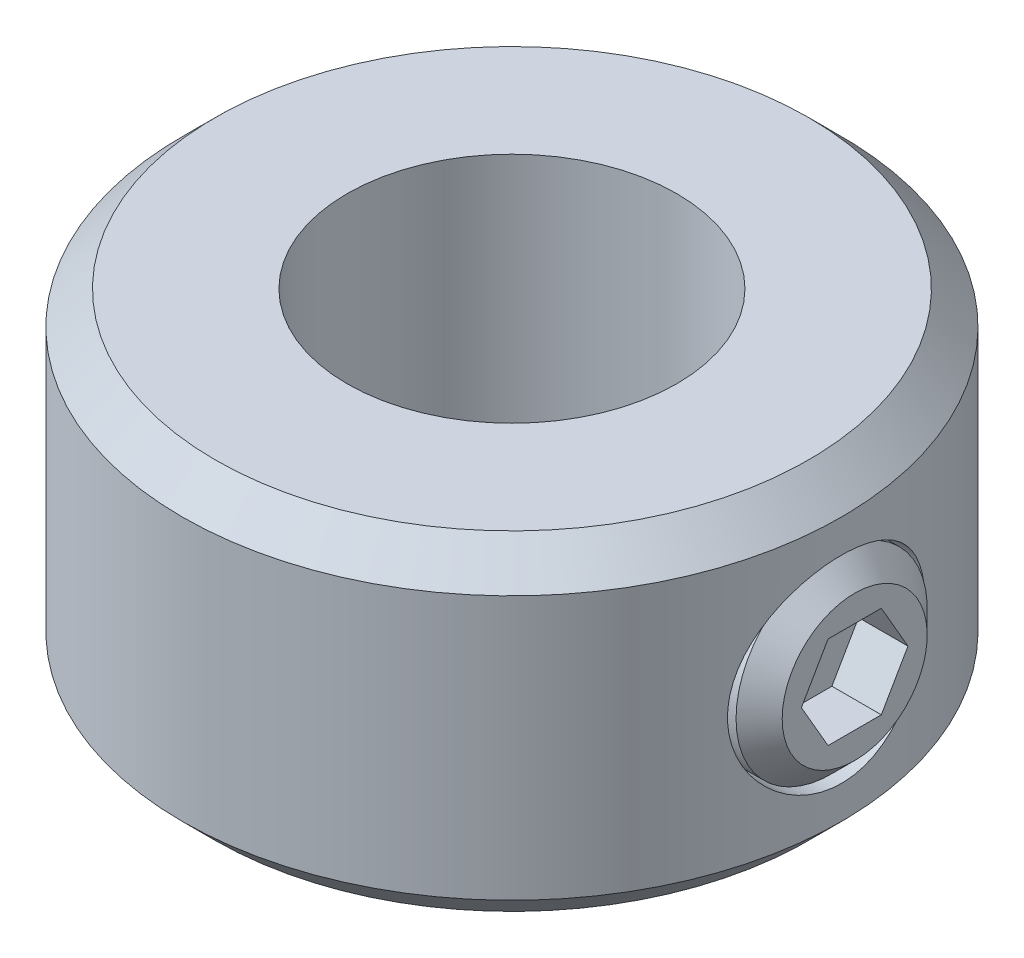
SolidWorks part; units mm, degrees
ref_plane "Front Plane" through (0, 0, 0) normal (0, 0, 1) x (1, 0, 0)
ref_plane "Top Plane" through (0, 0, 0) normal (0, 1, 0) x (1, 0, 0)
ref_plane "Right Plane" through (0, 0, 0) normal (1, 0, 0) x (0, 0, -1)
sketch "Sketch1" plane through (0, 0, 0) normal (0, 1, 0) x (1, 0, 0)
  circle A0 centre (0, 0) radius 2.5
  circle A1 centre (0, 0) radius 5
  dimension "D1" = 5
  dimension "D2" = 10
extrude "Boss-Extrude1" add sketch "Sketch1" along normal blind 5
ref_plane "Plane1" through (5, 0, 0) normal (1, 0, 0) x (0, 0, -1)
sketch "Sketch2" plane through (5, 0, 0) normal (1, 0, 0) x (0, 0, -1)
  line L0 (-5, 2.5) -> (5, 2.5) construction
  line L1 (-5, 5) -> (-5, 0) construction
  line L2 (5, 0) -> (5, 5) construction
  circle A0 centre (0, 2.5) radius 1.5
  dimension "D1" = 3
extrude "Cut-Extrude1" cut sketch "Sketch2" against normal up to surface (3 mm away)
chamfer "Chamfer1" distance 0.5 angle 45 2 edges at (0, 0, 5) (0, 5, 5)
ref_plane "Plane2" through (2.5, 0, 0) normal (-1, 0, 0) x (0, 0, 1)
sketch "Sketch3" plane through (2.5, 0, 0) normal (-1, 0, 0) x (0, 0, 1)
  circle A0 centre (0, 2.5) radius 1.45
  dimension "D1" = 2.9
extrude "Boss-Extrude3" add sketch "Sketch3" against normal blind 2.7
chamfer "Chamfer3" distance 0.35 angle 45 1 edges at (5.2, 2.5, 1.45)
sketch "Sketch4" plane through (5.2, 0, 0) normal (1, 0, 0) x (0, 0, -1)
  line L1 (0.8083, 2.5) -> (0.4041, 3.2)
  line L2 (0.4041, 3.2) -> (-0.4041, 3.2)
  line L3 (-0.4041, 3.2) -> (-0.8083, 2.5)
  line L4 (-0.8083, 2.5) -> (-0.4041, 1.8)
  line L5 (-0.4041, 1.8) -> (0.4041, 1.8)
  line L6 (0.4041, 1.8) -> (0.8083, 2.5)
  circle A0 centre (0, 2.5) radius 0.7 construction
  dimension "D1" = 1.4
extrude "Cut-Extrude2" cut sketch "Sketch4" against normal blind 0.75
